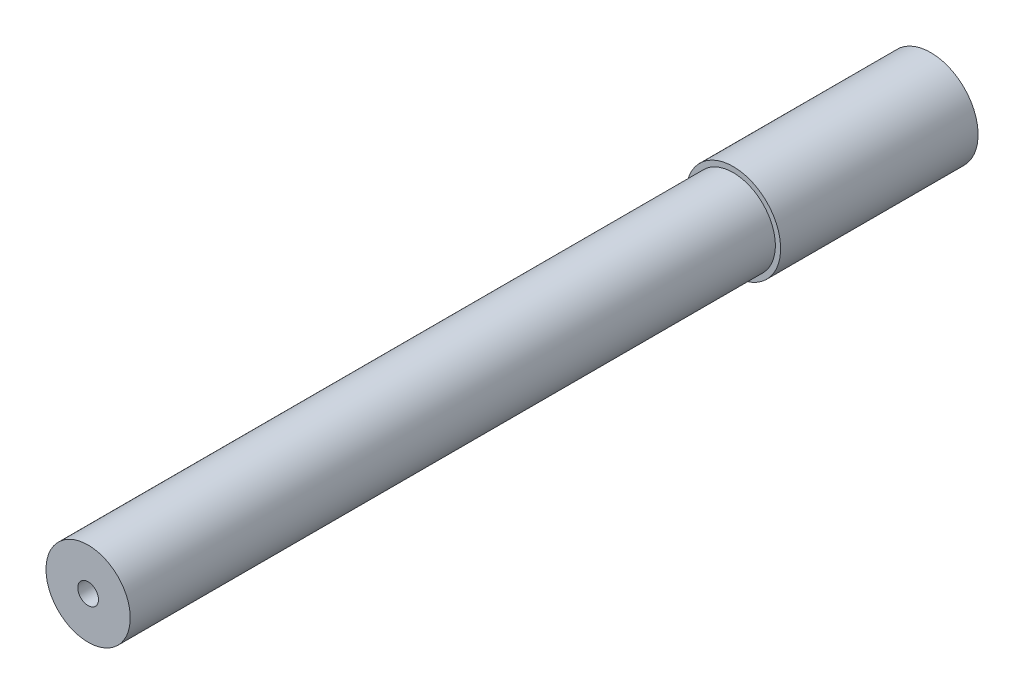
SolidWorks part; units mm, degrees
material "PET"
ref_plane "Front Plane" through (0, 0, 0) normal (0, 0, 1) x (1, 0, 0)
ref_plane "Top Plane" through (0, 0, 0) normal (0, 1, 0) x (1, 0, 0)
ref_plane "Right Plane" through (0, 0, 0) normal (1, 0, 0) x (0, 0, -1)
sketch "Sketch2" plane through (0, 0, 0) normal (0, 0, 1) x (1, 0, 0)
  circle A0 centre (0, 0) radius 9.144
  dimension "D1" = 18.288
extrude "Thicker Section" add sketch "Sketch2" along normal blind 38.1
sketch "Sketch3" plane through (0, 0, 38.1) normal (0, 0, 1) x (1, 0, 0)
  circle A0 centre (0, 0) radius 8.128
  dimension "D1" = 16.256
extrude "Smaller  Section" add sketch "Sketch3" along normal blind 124.46
fillet "Fillet1" [suppressed] radius 2.54
sketch "Sketch4" plane through (0, 0, 162.56) normal (0, 0, 1) x (1, 0, 0)
  circle A0 centre (0, 0) radius 2
  dimension "D1" = 4
extrude "Cut-Extrude1" cut sketch "Sketch4" against normal blind 19.05
